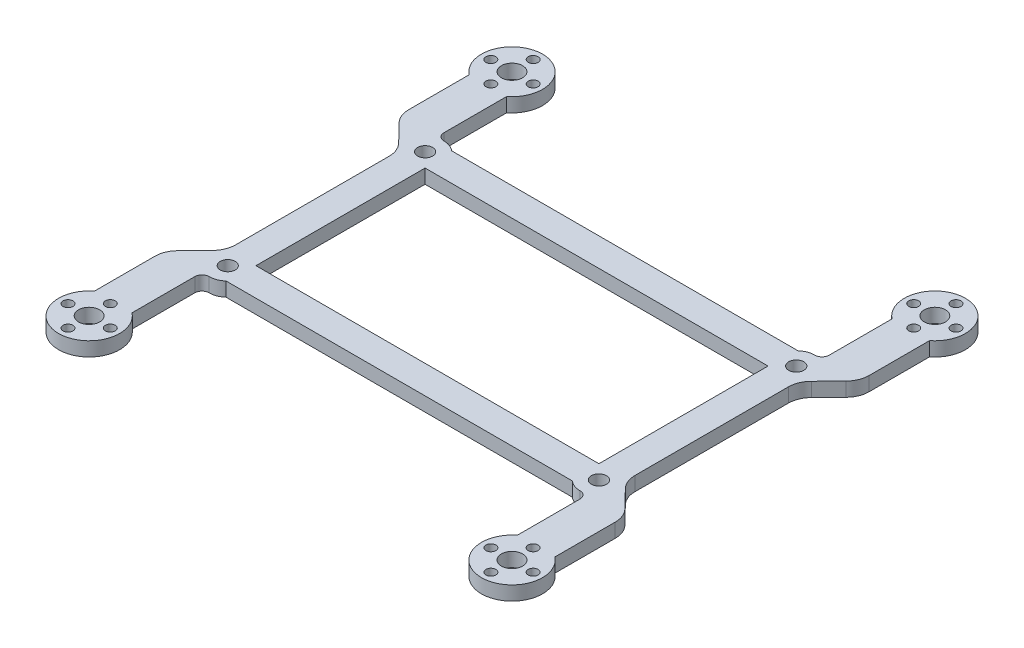
SolidWorks part; units mm, degrees
ref_plane "前视基准面" through (0, 0, 0) normal (0, 0, 1) x (1, 0, 0)
ref_plane "上视基准面" through (0, 0, 0) normal (0, 1, 0) x (1, 0, 0)
ref_plane "右视基准面" through (0, 0, 0) normal (1, 0, 0) x (0, 0, -1)
other "Configuration Table"
sketch "草图1" plane through (0, 0, 0) normal (0, 1, 0) x (1, 0, 0)
  line L0 (49, -45) -> (49, 45) construction
  line L1 (-45, -45) -> (45, -45) construction
  line L2 (-45, -45) -> (-45, 45) construction
  line L3 (-45, 45) -> (45, 45) construction
  line L4 (45, -45) -> (45, 45) construction
  line L5 (-45, -45) -> (45, 45) construction
  line L6 (-45, 45) -> (45, -45) construction
  line L7 (-43.5, -25) -> (43.5, -25) construction
  line L8 (-43.5, -25) -> (-43.5, 25) construction
  line L9 (-43.5, 25) -> (43.5, 25) construction
  line L10 (43.5, -25) -> (43.5, 25) construction
  line L11 (-43.5, -25) -> (43.5, 25) construction
  line L12 (-43.5, 25) -> (43.5, -25) construction
  line L13 (-10, -10) -> (10, -10) construction
  line L14 (-10, -10) -> (-10, 10) construction
  line L15 (-10, 10) -> (10, 10) construction
  line L16 (10, -10) -> (10, 10) construction
  line L17 (-10, -10) -> (10, 10) construction
  line L18 (-10, 10) -> (10, -10) construction
  line L19 (41, -45) -> (41, 45) construction
  line L20 (41, 39.8765) -> (41, 26.5)
  line L21 (43.9235, 19.8039) -> (47.5765, 23.5429)
  line L22 (49, 39.8765) -> (49, 27.037)
  line L23 (0, 0) -> (14.7512, 0) construction
  line L24 (41, -26.5) -> (41, -39.8765)
  line L25 (49, -39.8765) -> (49, -27.037)
  line L26 (47.5765, -23.5429) -> (43.9235, -19.8039)
  line L27 (0, 0) -> (0, 21.9355) construction
  line L28 (-49, -45) -> (-49, 45) construction
  line L29 (-41, -45) -> (-41, 45) construction
  line L30 (-45, -45) -> (-45, 45) construction
  line L31 (-41, -26.5) -> (-41, -39.8765)
  line L32 (-49, -39.8765) -> (-49, -27.037)
  line L33 (-47.5765, -23.5429) -> (-43.9235, -19.8039)
  line L34 (-49, 39.8765) -> (-49, 27.037)
  line L35 (-47.5765, 23.5429) -> (-43.9235, 19.8039)
  line L36 (-41, 39.8765) -> (-41, 26.5)
  line L37 (-39.5, 21) -> (39.5, 21) construction
  line L38 (39.5, 21) -> (39.5, -21) construction
  line L39 (-39.5, 21) -> (-39.5, -21) construction
  line L40 (-39.5, -21) -> (39.5, -21) construction
  line L42 (42.5, 16.3098) -> (42.5, -16.3098)
  line L44 (-42.5, 16.3098) -> (-42.5, -16.3098)
  line L45 (-36.5, -18) -> (36.5, -18)
  line L46 (36.5, 18) -> (36.5, -18)
  line L47 (-36.5, 18) -> (36.5, 18)
  line L48 (-36.5, 18) -> (-36.5, -18)
  line L49 (-42.5, 24) -> (-42.5, -24) construction
  line L50 (-36.8542, 24) -> (36.8542, 24)
  line L51 (-42.5, 24) -> (42.5, 24) construction
  line L52 (42.5, 24) -> (42.5, -24) construction
  line L53 (-36.8542, -24) -> (36.8542, -24)
  line L54 (-42.5, -24) -> (42.5, -24) construction
  circle A0 centre (45, 45) radius 31.5 construction
  circle A1 centre (-45, 45) radius 31.5 construction
  circle A2 centre (-45, -45) radius 31.5 construction
  circle A3 centre (45, -45) radius 31.5 construction
  circle A4 centre (-45, 45) radius 9.5 construction
  circle A5 centre (45, 45) radius 9.5 construction
  circle A6 centre (45, -45) radius 9.5 construction
  circle A7 centre (-45, -45) radius 9.5 construction
  circle A8 centre (-39.5, 21) radius 1.6
  circle A9 centre (39.5, 21) radius 1.6
  circle A10 centre (39.5, -21) radius 1.6
  circle A11 centre (-39.5, -21) radius 1.6
  circle A12 centre (-10, 10) radius 1.6 construction
  circle A13 centre (10, 10) radius 1.6 construction
  circle A14 centre (-10, -10) radius 1.6 construction
  circle A15 centre (10, -10) radius 1.6 construction
  arc A16 (49, 39.8765) -> (41, 39.8765) centre (45, 45) ccw
  arc A17 (-41, 39.8765) -> (-49, 39.8765) centre (-45, 45) ccw
  arc A18 (-49, -39.8765) -> (-41, -39.8765) centre (-45, -45) ccw
  arc A19 (41, -39.8765) -> (49, -39.8765) centre (45, -45) ccw
  arc A20 (39.5, 25) -> (36.8542, 24) centre (39.5, 21) ccw
  arc A22 (41, 26.5) -> (39.5, 25) centre (39.5, 26.5) cw
  arc A23 (41, -26.5) -> (39.5, -25) centre (39.5, -26.5) ccw
  arc A24 (-36.8542, 24) -> (-39.5, 25) centre (-39.5, 21) ccw
  arc A25 (-39.5, -25) -> (-36.8542, -24) centre (-39.5, -21) ccw
  arc A26 (-41, -26.5) -> (-39.5, -25) centre (-39.5, -26.5) cw
  arc A27 (-41, 26.5) -> (-39.5, 25) centre (-39.5, 26.5) ccw
  arc A28 (-49, -27.037) -> (-47.5765, -23.5429) centre (-44, -27.037) cw
  arc A29 (36.8542, -24) -> (39.5, -25) centre (39.5, -21) ccw
  arc A30 (49, -27.037) -> (47.5765, -23.5429) centre (44, -27.037) ccw
  arc A31 (47.5765, 23.5429) -> (49, 27.037) centre (44, 27.037) ccw
  arc A32 (-49, 27.037) -> (-47.5765, 23.5429) centre (-44, 27.037) ccw
  arc A33 (43.9235, -19.8039) -> (42.5, -16.3098) centre (47.5, -16.3098) cw
  arc A34 (43.9235, 19.8039) -> (42.5, 16.3098) centre (47.5, 16.3098) ccw
  arc A35 (-42.5, -16.3098) -> (-43.9235, -19.8039) centre (-47.5, -16.3098) cw
  arc A36 (-42.5, 16.3098) -> (-43.9235, 19.8039) centre (-47.5, 16.3098) ccw
  circle A37 centre (45, 45) radius 2.25
  circle A38 centre (45, 49.5) radius 1.05
  circle A39 centre (49.5, 45) radius 1.05
  circle A40 centre (45, 40.5) radius 1.05
  circle A41 centre (40.5, 45) radius 1.05
  circle A42 centre (40.5, -45) radius 1.05
  circle A43 centre (45, -40.5) radius 1.05
  circle A44 centre (49.5, -45) radius 1.05
  circle A45 centre (45, -49.5) radius 1.05
  circle A46 centre (45, -45) radius 2.25
  circle A47 centre (-45, -40.5) radius 1.05
  circle A48 centre (-40.5, -45) radius 1.05
  circle A49 centre (-45, -49.5) radius 1.05
  circle A50 centre (-49.5, -45) radius 1.05
  circle A51 centre (-45, -45) radius 2.25
  circle A52 centre (-40.5, 45) radius 1.05
  circle A53 centre (-45, 40.5) radius 1.05
  circle A54 centre (-49.5, 45) radius 1.05
  circle A55 centre (-45, 49.5) radius 1.05
  circle A56 centre (-45, 45) radius 2.25
  point P0 (0, 0)
  point P19 (0, 0)
  point P32 (0, 0)
  point P93 (0, 0)
  point P104 (-49, -25)
  point P107 (49, -25)
  point P110 (49, 25)
  point P113 (-49, 25)
  point P125 (45, 45)
  point P156 (0, 0)
  dimension "D3" = 63
  dimension "D4" = 63
  dimension "D5" = 63
  dimension "D6" = 63
  dimension "D7" = 19
  dimension "D8" = 19
  dimension "D9" = 19
  dimension "D10" = 19
  dimension "D15" = 3.2
  dimension "D18" = 3.2
  dimension "D21" = 3.2
  dimension "D24" = 3.2
  dimension "D27" = 3.2
  dimension "D28" = 3.2
  dimension "D29" = 3.2
  dimension "D30" = 3.2
  dimension "D31" = 13
  dimension "D32" = 13
  dimension "D33" = 13
  dimension "D34" = 13
  dimension "D35" = 8
  dimension "D36" = 3
  dimension "D17" = 8
  dimension "D23" = 8
  dimension "D39" = 5
  dimension "D40" = 5
  dimension "D41" = 4.5
  dimension "D42" = 2.1
  dimension "D44" = 4
  dimension "D1" = 90
  dimension "D2" = 90
  dimension "D11" = 87
  dimension "D12" = 50
  dimension "D13" = 3
  dimension "D14" = 4
  dimension "D16" = 4
  dimension "D19" = 3
  dimension "D20" = 4
  dimension "D22" = 4
  dimension "D25" = 20
  dimension "D26" = 20
  dimension "D43" = 4.5
  dimension "D37" = 4
  dimension "D38" = 4
  dimension "D45" = 4
extrude "凸台-拉伸2" add sketch "草图1" along normal blind 3
